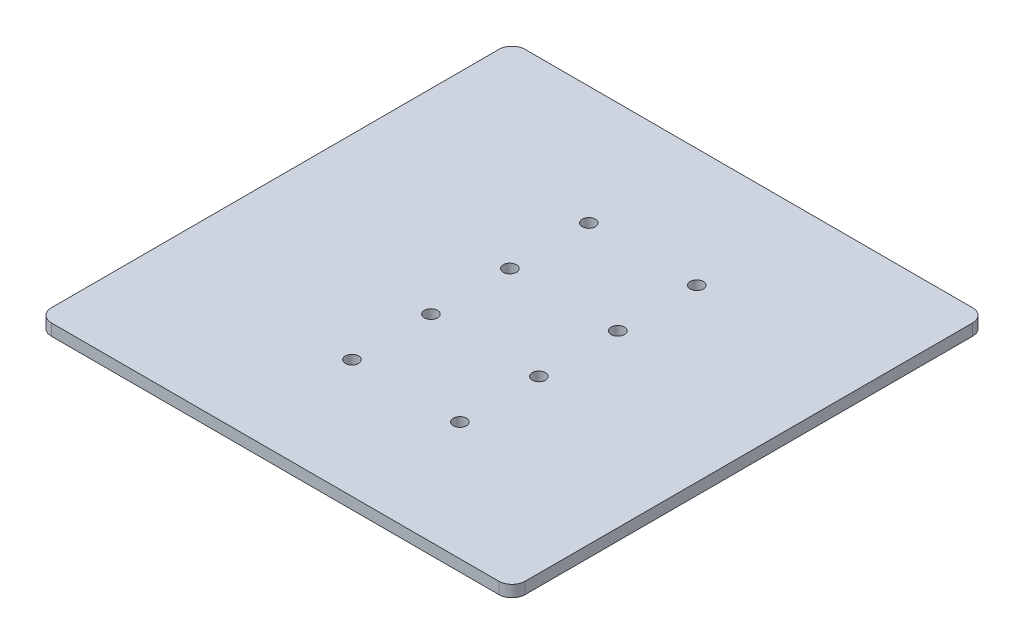
SolidWorks part; units mm, degrees
ref_plane "Front Plane" through (0, 0, 0) normal (0, 0, 1) x (1, 0, 0)
ref_plane "Top Plane" through (0, 0, 0) normal (0, 1, 0) x (1, 0, 0)
ref_plane "Right Plane" through (0, 0, 0) normal (1, 0, 0) x (0, 0, -1)
sketch "Sketch1" plane through (0, 0, 0) normal (0, 1, 0) x (1, 0, 0)
  line L1 (114.3, 114.3) -> (-114.3, 114.3)
  line L2 (114.3, 114.3) -> (114.3, -114.3)
  line L3 (114.3, -114.3) -> (-114.3, -114.3)
  line L4 (-114.3, 114.3) -> (-114.3, -114.3)
  line L5 (114.3, 114.3) -> (-114.3, -114.3) construction
  line L6 (114.3, -114.3) -> (-114.3, 114.3) construction
  point P0 (0, 0)
  dimension "D1" = 228.6
  dimension "D2" = 228.6
extrude "Boss-Extrude1" add sketch "Sketch1" along normal blind 5.588
hole_wizard "1/4 (0.25) Diameter Hole1" positions "Sketch4" profile "Sketch5" hole size "1/4" standard "ANSI Inch" end condition through all
sketch "Sketch4" plane through (0, 5.588, 0) normal (0, 1, 0) x (1, 0, 0)
  line L0 (-114.3, 114.3) -> (-114.3, -114.3) construction
  line L1 (114.3, 114.3) -> (-114.3, 114.3) construction
  point P0 (-20.066, 57.15)
  point P7 (32.004, 57.15)
  dimension "D1" = 94.234
  dimension "D2" = 57.15
  dimension "D3" = 52.07
sketch "Sketch5" plane through (-20.066, 5.588, -57.15) normal (1, 0, 0) x (0, 0, 1)
  line L0 (0, 0) -> (0, 5.588)
  line L1 (0, 5.588) -> (3.175, 5.588)
  line L2 (3.175, 5.588) -> (3.175, 0)
  line L5 (3.175, 0) -> (0, 0)
  line L11 (0, -6.35) -> (0, 107.95) construction
  dimension "Thru Hole Dia." = 6.35
  dimension "Thru Hole Depth" = 5.588
pattern_linear "LPattern1" count 4 spacing 38.1 along (0, 0, 1) of "1/4 (0.25) Diameter Hole1"
fillet "Fillet1" radius 6.35 4 edges at (-114.3, 2.794, -114.3) (114.3, 2.794, -114.3) (114.3, 2.794, 114.3) (-114.3, 2.794, 114.3)
